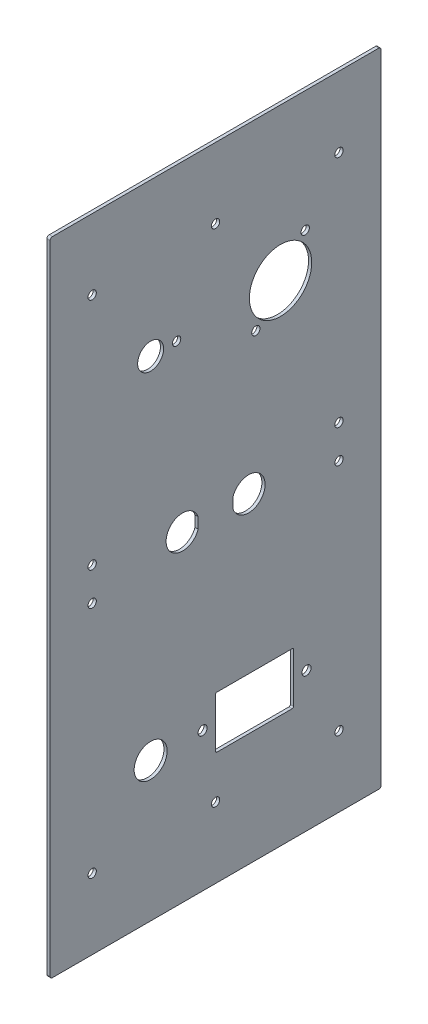
SolidWorks part; units mm, degrees
material "AISI 1020 Steel, Cold Rolled"
ref_plane "Front Plane" through (0, 0, 0) normal (0, 0, 1) x (1, 0, 0)
ref_plane "Top Plane" through (0, 0, 0) normal (0, 1, 0) x (1, 0, 0)
ref_plane "Right Plane" through (0, 0, 0) normal (1, 0, 0) x (0, 0, -1)
sketch "Sketch1" plane through (0, 0, 0) normal (1, 0, 0) x (0, 0, -1)
  line L0 (-62.8, -237.66) -> (62.8, -237.66) construction
  line L1 (62.8, 9.9) -> (-62.8, 9.9) construction
  line L2 (-62.8, -237.66) -> (62.8, -237.66) construction
  line L3 (62.8, 9.9) -> (-62.8, 9.9) construction
  line L4 (63.943, -236.517) -> (63.943, 8.757) construction
  line L5 (-63.943, 8.757) -> (-63.943, -236.517) construction
  line L10 (62.8, 9.646) -> (-62.8, 9.646)
  line L11 (-63.689, 8.757) -> (-63.689, -236.517)
  line L12 (-62.8, -237.406) -> (62.8, -237.406)
  line L13 (63.689, -236.517) -> (63.689, 8.757)
  arc A0 (-63.943, -236.517) -> (-62.8, -237.66) centre (-62.8, -236.517) ccw construction
  arc A1 (62.8, -237.66) -> (63.943, -236.517) centre (62.8, -236.517) ccw construction
  arc A2 (-62.8, 9.9) -> (-63.943, 8.757) centre (-62.8, 8.757) ccw construction
  arc A3 (63.943, 8.757) -> (62.8, 9.9) centre (62.8, 8.757) ccw construction
  arc A4 (-63.943, -236.517) -> (-62.8, -237.66) centre (-62.8, -236.517) ccw construction
  arc A5 (62.8, -237.66) -> (63.943, -236.517) centre (62.8, -236.517) ccw construction
  arc A6 (-62.8, 9.9) -> (-63.943, 8.757) centre (-62.8, 8.757) ccw construction
  arc A7 (63.943, 8.757) -> (62.8, 9.9) centre (62.8, 8.757) ccw construction
  arc A12 (-62.8, 9.646) -> (-63.689, 8.757) centre (-62.8, 8.757) ccw
  arc A13 (-63.689, -236.517) -> (-62.8, -237.406) centre (-62.8, -236.517) ccw
  arc A14 (62.8, -237.406) -> (63.689, -236.517) centre (62.8, -236.517) ccw
  arc A15 (63.689, 8.757) -> (62.8, 9.646) centre (62.8, 8.757) ccw
  dimension "D1" = 0.254
extrude "Boss-Extrude1" add sketch "Sketch1" against normal blind 1.22 contours L4 A7 L3 A6 L5 A4 L2 A5 | L13 A15 L10 A12 L11 A13 L12 A14
sketch "Sketch3" plane through (0, 0, 0) normal (1, 0, 0) x (0, 0, -1)
  circle A1 centre (47.5, -107.5) radius 1.6
  circle A2 centre (47.5, -107.5) radius 1.6
  circle A3 centre (-47.5, -107.5) radius 1.6
  circle A4 centre (-47.5, -107.5) radius 1.6
  circle A5 centre (47.5, -17.5) radius 1.6
  circle A6 centre (47.5, -17.5) radius 1.6
  circle A7 centre (0, -17.5) radius 1.6
  circle A8 centre (0, -17.5) radius 1.6
  circle A9 centre (-47.5, -17.5) radius 1.6
  circle A10 centre (-47.5, -17.5) radius 1.6
  circle A11 centre (-47.5, -210.26) radius 1.6
  circle A12 centre (-47.5, -210.26) radius 1.6
  circle A13 centre (0, -210.26) radius 1.6
  circle A14 centre (0, -210.26) radius 1.6
  circle A15 centre (47.5, -210.26) radius 1.6
  circle A16 centre (47.5, -210.26) radius 1.6
  circle A17 centre (-47.5, -120.26) radius 1.6
  circle A18 centre (-47.5, -120.26) radius 1.6
  circle A19 centre (47.5, -120.26) radius 1.6
  circle A20 centre (47.5, -120.26) radius 1.6
  dimension "D1" = 0
  dimension "D2" = 0
  dimension "D3" = 0
  dimension "D4" = 0
  dimension "D5" = 0
  dimension "D6" = 0
  dimension "D7" = 0
  dimension "D8" = 0
  dimension "D9" = 0
  dimension "D10" = 0
extrude "Cut-Extrude1" cut sketch "Sketch3" against normal through all
sketch "Sketch4" plane through (0, 0, 0) normal (1, 0, 0) x (0, 0, -1)
  line L0 (35, -183.88) -> (-5, -183.88) construction
  line L2 (0.5, -193.88) -> (29.5, -193.88)
  line L3 (0, -193.38) -> (0, -174.38)
  line L4 (0.5, -173.88) -> (29.5, -173.88)
  line L5 (30, -193.38) -> (30, -174.38)
  line L6 (0, -193.88) -> (30, -173.88) construction
  line L7 (0, -173.88) -> (30, -193.88) construction
  line L8 (6.7, -111.8009) -> (6.7, -115.9591)
  line L9 (-6.7, -111.8009) -> (-6.7, -115.9591)
  circle A0 centre (25, -48.88) radius 12
  circle A1 centre (-25, -49.13) radius 5
  arc A2 (6.7, -115.9591) -> (6.7, -111.8009) centre (12.7, -113.88) ccw
  arc A3 (-6.7, -111.8009) -> (-6.7, -115.9591) centre (-12.7, -113.88) ccw
  circle A4 centre (35, -183.88) radius 1.75
  circle A5 centre (-5, -183.88) radius 1.75
  circle A6 centre (34.5, -36.88) radius 1.6
  circle A7 centre (15.5, -60.88) radius 1.6
  circle A8 centre (-15, -49.13) radius 1.6
  arc A9 (0.5, -193.88) -> (0, -193.38) centre (0.5, -193.38) cw
  arc A10 (29.5, -193.88) -> (30, -193.38) centre (29.5, -193.38) ccw
  arc A11 (0, -174.38) -> (0.5, -173.88) centre (0.5, -174.38) cw
  arc A12 (29.5, -173.88) -> (30, -174.38) centre (29.5, -174.38) cw
  circle A13 centre (-25, -183.88) radius 6.35
  arc A14 (-6.7, -115.9591) -> (-6.7, -111.8009) centre (-12.7, -113.88) ccw construction
  arc A15 (6.7, -111.8009) -> (6.7, -115.9591) centre (12.7, -113.88) ccw construction
  point P7 (0, 0)
  point P10 (0, 0)
  point P27 (15, -183.88)
  point P52 (15, -183.88)
  dimension "D1" = 12.7
  dimension "D2" = 24
  dimension "D3" = 3.2
  dimension "D4" = 3.2
  dimension "D5" = 10
  dimension "D6" = 3.5
  dimension "D9" = 0.5
  dimension "D10" = 12.7
  dimension "D7" = 20
  dimension "D8" = 30
  dimension "D11" = 6
  dimension "D12" = 6
  dimension "D13" = 40
extrude "Cut-Extrude2" cut sketch "Sketch4" against normal through all
equation "\"D12@Sketch4\"=\"D11@Sketch4\""
